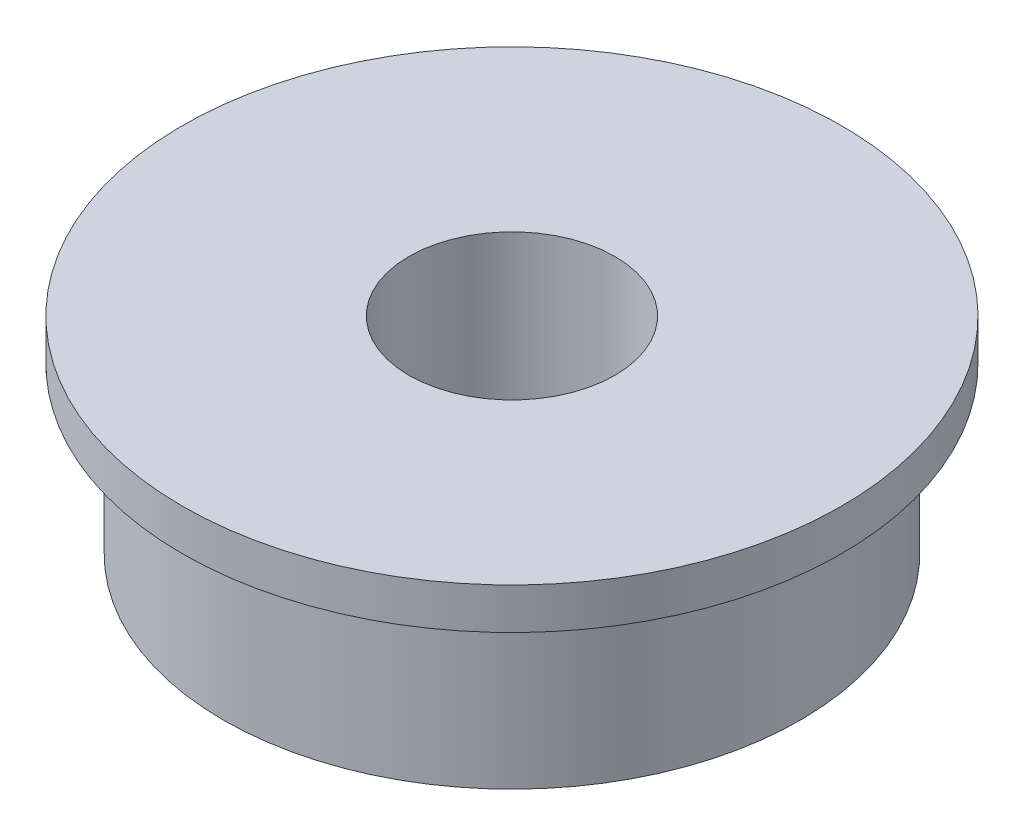
SolidWorks part; units mm, degrees
ref_plane "정면" through (0, 0, 0) normal (0, 0, 1) x (1, 0, 0)
ref_plane "윗면" through (0, 0, 0) normal (0, 1, 0) x (1, 0, 0)
ref_plane "우측면" through (0, 0, 0) normal (1, 0, 0) x (0, 0, -1)
sketch "스케치1" plane through (0, 0, 0) normal (0, 1, 0) x (1, 0, 0)
  circle A0 centre (0, 0) radius 2.5
  circle A1 centre (0, 0) radius 7
  dimension "D1" = 5
  dimension "D2" = 14
extrude "보스-돌출1" add sketch "스케치1" along normal blind 5
sketch "스케치2" plane through (0, 5, 0) normal (0, 1, 0) x (1, 0, 0)
  circle A0 centre (0, 0) radius 5.7232
  circle A1 centre (0, 0) radius 8
  dimension "D1" = 16
extrude "보스-돌출2" add sketch "스케치2" against normal blind 1
